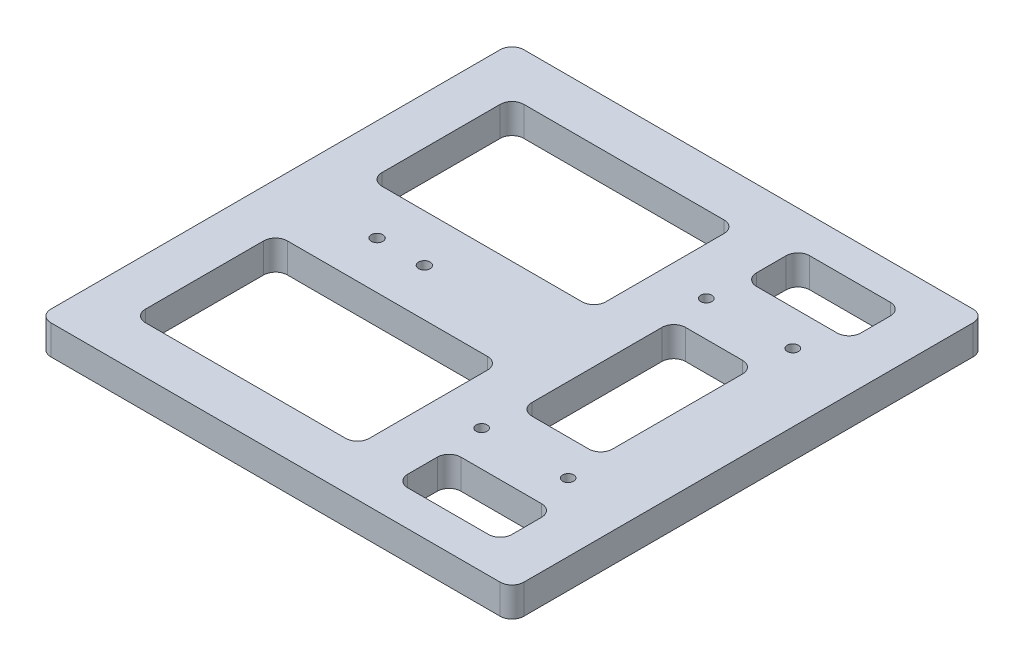
SolidWorks part; units mm, degrees
ref_plane "Front Plane" through (0, 0, 0) normal (0, 0, 1) x (1, 0, 0)
ref_plane "Top Plane" through (0, 0, 0) normal (0, 1, 0) x (1, 0, 0)
ref_plane "Right Plane" through (0, 0, 0) normal (1, 0, 0) x (0, 0, -1)
sketch "Base" plane through (0, 0, 0) normal (0, 1, 0) x (1, 0, 0)
  line L1 (-50.8, 50.8) -> (50.8, 50.8)
  line L2 (-50.8, 50.8) -> (-50.8, -50.8)
  line L3 (-50.8, -50.8) -> (50.8, -50.8)
  line L4 (50.8, 50.8) -> (50.8, -50.8)
  line L5 (-50.8, 50.8) -> (50.8, -50.8) construction
  line L6 (-50.8, -50.8) -> (50.8, 50.8) construction
  point P0 (0, 0)
  dimension "D1" = 101.6
  dimension "D2" = 101.6
ref_plane "Plane1" through (0, 50.8, 0) normal (0, 1, 0) x (1, 0, 0)
extrude "Boss-Extrude2" add sketch "Base" along normal blind 6.35
sketch "Sketch1" plane through (0, 6.35, 0) normal (0, 1, 0) x (1, 0, 0)
  line L1 (15.6972, 26.035) -> (38.1, 26.035) construction
  line L2 (15.6972, 26.035) -> (15.6972, -26.035) construction
  line L3 (15.6972, -26.035) -> (38.1, -26.035) construction
  line L4 (38.1, 26.035) -> (38.1, -26.035) construction
  line L5 (15.6972, 26.035) -> (38.1, -26.035) construction
  line L6 (15.6972, -26.035) -> (38.1, 26.035) construction
  line L7 (19.5072, 22.225) -> (19.5072, -22.225) construction
  line L8 (19.5072, -22.225) -> (34.29, -22.225) construction
  line L9 (34.29, 22.225) -> (34.29, -22.225) construction
  line L10 (19.5072, 22.225) -> (34.29, 22.225) construction
  line L11 (26.8986, 0) -> (26.8986, 26.035) construction
  line L12 (50.8, -50.8) -> (50.8, 50.8) construction
  line L13 (26.8986, 0) -> (38.1, 0) construction
  line L14 (-28.9814, 0) -> (-18.8214, 0) construction
  circle A0 centre (17.6022, 24.13) radius 1.1938
  circle A2 centre (36.195, 24.13) radius 1.1938
  circle A4 centre (17.6022, -24.13) radius 1.1938
  circle A5 centre (36.195, -24.13) radius 1.1938
  circle A6 centre (-28.9814, 0) radius 1.2446
  circle A7 centre (-18.8214, 0) radius 1.2446
  point P0 (26.8986, 0)
  point P27 (-23.9014, 0)
  dimension "D4" = 2.3876
  dimension "D8" = 2.4892
  dimension "D1" = 22.4028
  dimension "D2" = 52.07
  dimension "D5" = 1.905
  dimension "D6" = 12.7
  dimension "D3" = 3.81
  dimension "D7" = 1.905
  dimension "D9" = 10.16
  dimension "D10" = 50.8
extrude "Cut-Extrude1" cut sketch "Sketch1" against normal through all
fillet "Fillet1" radius 2.54 4 edges at (-50.8, 3.175, -50.8) (50.8, 3.175, -50.8) (-50.8, 3.175, 50.8) (50.8, 3.175, 50.8)
sketch "Sketch2" plane through (0, 0, 0) normal (0, -1, 0) x (1, 0, 0)
  circle A0 centre (17.6022, 24.13) radius 2.794
  circle A1 centre (36.195, 24.13) radius 2.794
  circle A2 centre (36.195, -24.13) radius 2.794
  circle A3 centre (17.6022, -24.13) radius 2.794
  circle A4 centre (-18.8214, 0) radius 2.794
  circle A5 centre (-28.9814, 0) radius 2.794
  dimension "D1" = 5.588
extrude "Cut-Extrude2" cut sketch "Sketch2" against normal blind 2.032
sketch "Sketch3" plane through (0, 6.35, 0) normal (0, 1, 0) x (1, 0, 0)
  line L0 (-50.8, 48.26) -> (-50.8, -48.26) construction
  line L1 (-38.1, -10.16) -> (4.9022, -10.16)
  line L2 (-40.64, -12.7) -> (-40.64, -38.1)
  line L3 (-38.1, -40.64) -> (4.9022, -40.64)
  line L4 (7.4422, -12.7) -> (7.4422, -38.1)
  line L5 (-40.64, -10.16) -> (7.4422, -40.64) construction
  line L6 (-40.64, -40.64) -> (7.4422, -10.16) construction
  line L7 (-48.26, -50.8) -> (48.26, -50.8) construction
  line L8 (-28.9814, 0) -> (-18.8214, 0) construction
  line L9 (-38.1, 40.64) -> (4.9022, 40.64)
  line L10 (7.4422, 12.7) -> (7.4422, 38.1)
  line L11 (-38.1, 10.16) -> (4.9022, 10.16)
  line L12 (-40.64, 12.7) -> (-40.64, 38.1)
  line L13 (50.8, -48.26) -> (50.8, 48.26) construction
  line L14 (20.7772, 16.51) -> (33.02, 16.51)
  line L15 (18.2372, 13.97) -> (18.2372, -13.97)
  line L16 (20.7772, -16.51) -> (33.02, -16.51)
  line L17 (35.56, 13.97) -> (35.56, -13.97)
  line L18 (18.2372, 16.51) -> (35.56, -16.51) construction
  line L19 (18.2372, -16.51) -> (35.56, 16.51) construction
  line L20 (20.7772, 43.18) -> (38.1, 43.18)
  line L21 (18.2372, 40.64) -> (18.2372, 34.29)
  line L22 (20.7772, 31.75) -> (38.1, 31.75)
  line L23 (40.64, 40.64) -> (40.64, 34.29)
  line L24 (18.2372, 43.18) -> (40.64, 31.75) construction
  line L25 (18.2372, 31.75) -> (40.64, 43.18) construction
  line L26 (17.6022, -24.13) -> (36.195, -24.13) construction
  line L27 (17.6022, 24.13) -> (36.195, 24.13) construction
  line L28 (48.26, 50.8) -> (-48.26, 50.8) construction
  line L29 (20.7772, -31.75) -> (38.1, -31.75)
  line L30 (40.64, -40.64) -> (40.64, -34.29)
  line L31 (20.7772, -43.18) -> (38.1, -43.18)
  line L32 (18.2372, -40.64) -> (18.2372, -34.29)
  circle A0 centre (17.6022, -24.13) radius 1.1938 construction
  arc A1 (-40.64, -38.1) -> (-38.1, -40.64) centre (-38.1, -38.1) ccw
  arc A2 (4.9022, -40.64) -> (7.4422, -38.1) centre (4.9022, -38.1) ccw
  arc A3 (4.9022, -10.16) -> (7.4422, -12.7) centre (4.9022, -12.7) cw
  arc A4 (-38.1, -10.16) -> (-40.64, -12.7) centre (-38.1, -12.7) ccw
  arc A5 (4.9022, 40.64) -> (7.4422, 38.1) centre (4.9022, 38.1) cw
  arc A6 (4.9022, 10.16) -> (7.4422, 12.7) centre (4.9022, 12.7) ccw
  arc A7 (-40.64, 38.1) -> (-38.1, 40.64) centre (-38.1, 38.1) cw
  arc A8 (-38.1, 10.16) -> (-40.64, 12.7) centre (-38.1, 12.7) cw
  arc A9 (33.02, -16.51) -> (35.56, -13.97) centre (33.02, -13.97) ccw
  arc A10 (33.02, 16.51) -> (35.56, 13.97) centre (33.02, 13.97) cw
  arc A11 (20.7772, 16.51) -> (18.2372, 13.97) centre (20.7772, 13.97) ccw
  arc A12 (18.2372, -13.97) -> (20.7772, -16.51) centre (20.7772, -13.97) ccw
  arc A13 (18.2372, 34.29) -> (20.7772, 31.75) centre (20.7772, 34.29) ccw
  arc A14 (38.1, 31.75) -> (40.64, 34.29) centre (38.1, 34.29) ccw
  arc A15 (38.1, 43.18) -> (40.64, 40.64) centre (38.1, 40.64) cw
  arc A16 (20.7772, 43.18) -> (18.2372, 40.64) centre (20.7772, 40.64) ccw
  arc A17 (38.1, -31.75) -> (40.64, -34.29) centre (38.1, -34.29) cw
  arc A18 (38.1, -43.18) -> (40.64, -40.64) centre (38.1, -40.64) ccw
  arc A19 (18.2372, -34.29) -> (20.7772, -31.75) centre (20.7772, -34.29) cw
  arc A20 (20.7772, -43.18) -> (18.2372, -40.64) centre (20.7772, -40.64) cw
  point P0 (-16.5989, -25.4)
  point P39 (26.8986, 0)
  point P44 (29.4386, 37.465)
  point P56 (26.8986, -24.13)
  dimension "D5" = 2.54
  dimension "D12" = 2.54
  dimension "D1" = 10.16
  dimension "D2" = 10.16
  dimension "D3" = 10.16
  dimension "D4" = 10.16
  dimension "D6" = 15.24
  dimension "D7" = 15.24
  dimension "D8" = 7.62
  dimension "D9" = 10.16
  dimension "D10" = 7.62
  dimension "D11" = 7.62
extrude "Cut-Extrude3" cut sketch "Sketch3" against normal through all
